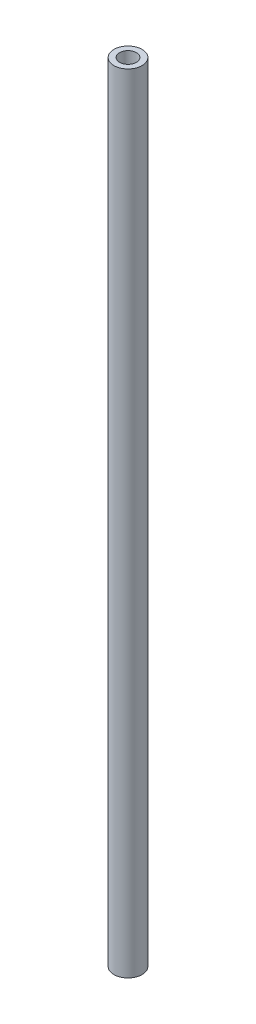
SolidWorks part; units mm, degrees
material "Zoltek Panex 33"
ref_plane "Front Plane" through (0, 0, 0) normal (0, 0, 1) x (1, 0, 0)
ref_plane "Top Plane" through (0, 0, 0) normal (0, 1, 0) x (1, 0, 0)
ref_plane "Right Plane" through (0, 0, 0) normal (1, 0, 0) x (0, 0, -1)
sketch "Sketch1" plane through (0, 0, 0) normal (0, 1, 0) x (1, 0, 0)
  circle A0 centre (0, 0) radius 2.5
  circle A1 centre (0, 0) radius 1.5
  dimension "D1" = 5
  dimension "D2" = 3
extrude "Boss-Extrude1" add sketch "Sketch1" along normal mid plane 140
